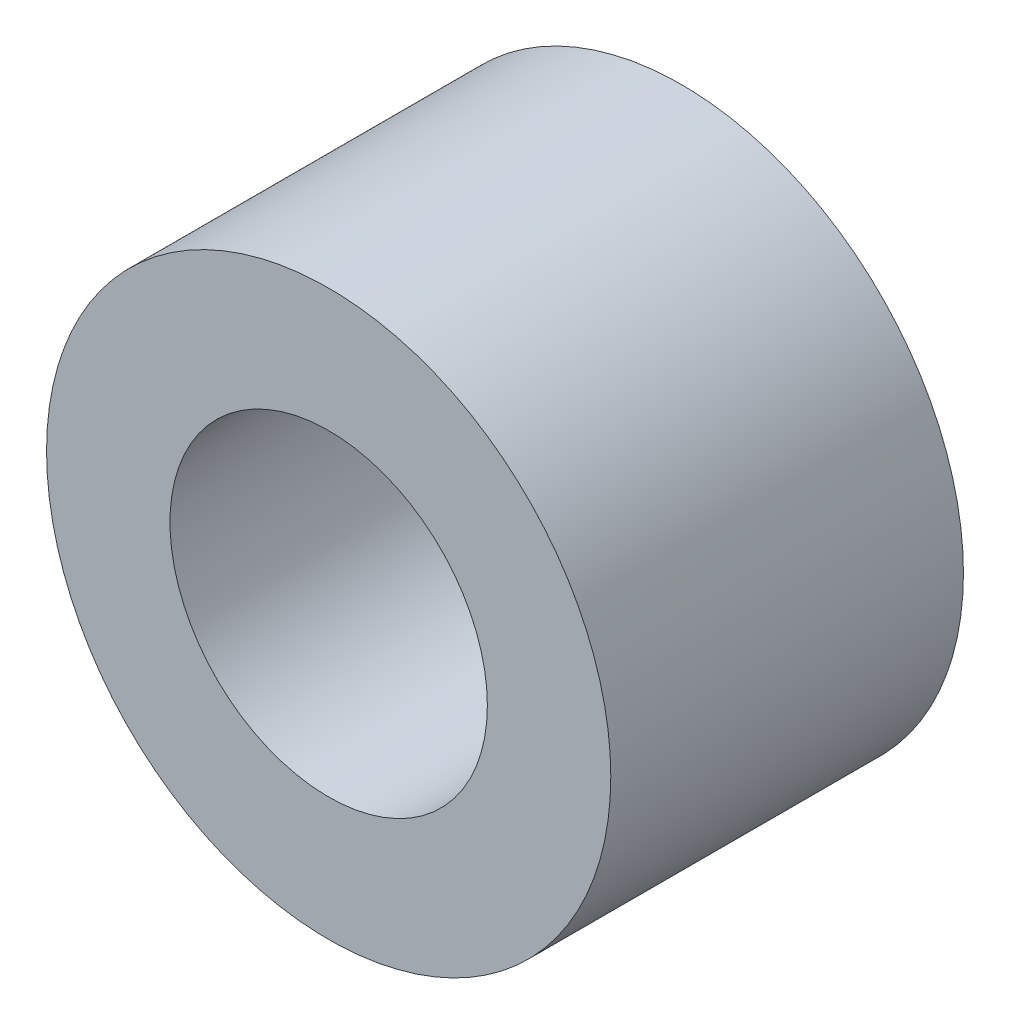
SolidWorks part; units mm, degrees
ref_plane "前视基准面" through (0, 0, 0) normal (0, 0, 1) x (1, 0, 0)
ref_plane "上视基准面" through (0, 0, 0) normal (0, 1, 0) x (1, 0, 0)
ref_plane "右视基准面" through (0, 0, 0) normal (1, 0, 0) x (0, 0, -1)
other "Configuration Table"
sketch "草图1" plane through (0, 0, 0) normal (0, 0, 1) x (1, 0, 0)
  circle A0 centre (0, 0) radius 4
  dimension "diameter" = 8
extrude "Cable_bulkhead" add sketch "草图1" along normal blind 5
sketch "草图2" plane through (0, 0, 5) normal (0, 0, 1) x (1, 0, 0)
  circle A0 centre (0, 0) radius 2.25
  dimension "diameter" = 4.5
extrude "Cable_passage" cut sketch "草图2" against normal through all
